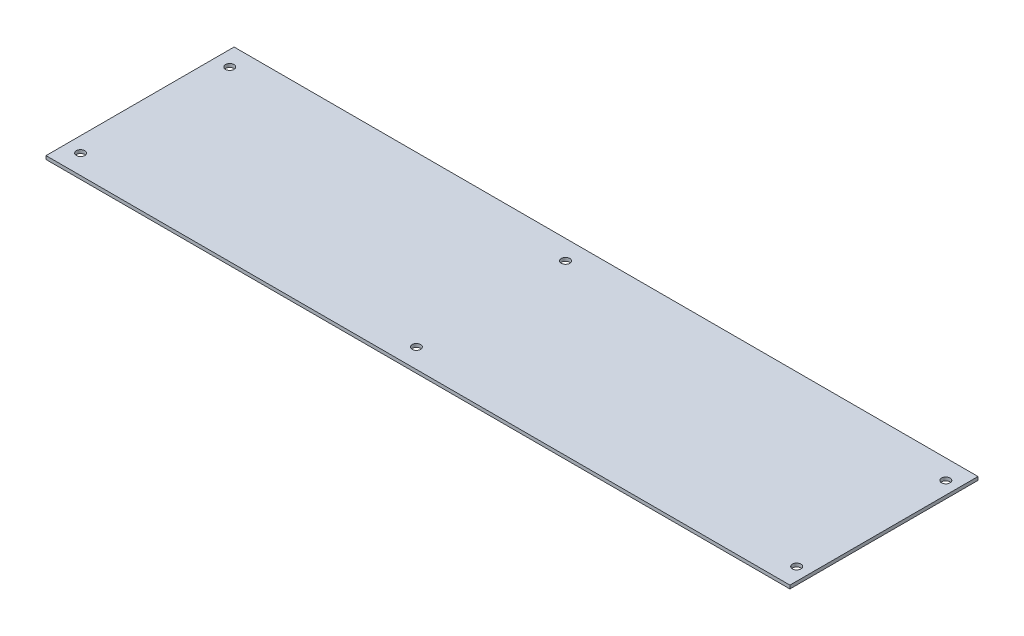
SolidWorks part; units mm, degrees
material "PC High Viscosity"
ref_plane "Front Plane" through (0, 0, 0) normal (0, 0, 1) x (1, 0, 0)
ref_plane "Top Plane" through (0, 0, 0) normal (0, 1, 0) x (1, 0, 0)
ref_plane "Right Plane" through (0, 0, 0) normal (1, 0, 0) x (0, 0, -1)
sketch "Sketch1" plane through (0, 0, 0) normal (0, 1, 0) x (1, 0, 0)
  line L1 (0, 0) -> (696.9125, 0)
  line L2 (0, 0) -> (0, -176.2125)
  line L3 (0, -176.2125) -> (696.9125, -176.2125)
  line L4 (696.9125, 0) -> (696.9125, -176.2125)
  dimension "D1" = 696.9125
  dimension "D2" = 176.2125
extrude "Boss-Extrude1" add sketch "Sketch1" along normal blind 3.175
extrude "Cut-Extrude1" cut sketch "Sketch2" against normal through all and the other way through all
sketch "Sketch2" plane through (324.8415, 3.175, 83.0995) normal (0, 1, 0) x (1, 0, 0)
  line L0 (360.1647, 83.8933) -> (360.1647, -93.9067) construction
  line L6 (347.4647, -5.0067) -> (371.2772, -5.0067) construction
  line L8 (3.9083, 83.8933) -> (3.9083, -93.9067) construction
  line L11 (-310.6722, 83.8933) -> (-310.6722, -93.9067) construction
  circle A0 centre (360.1647, 64.8433) radius 3.9688
  circle A1 centre (360.1647, -74.8567) radius 3.9688
  circle A3 centre (3.9083, 64.8433) radius 3.9687
  circle A4 centre (-310.6722, 64.8433) radius 3.9688
  circle A5 centre (3.9083, -74.8567) radius 3.9687
  circle A6 centre (-310.6722, -74.8567) radius 3.9688
